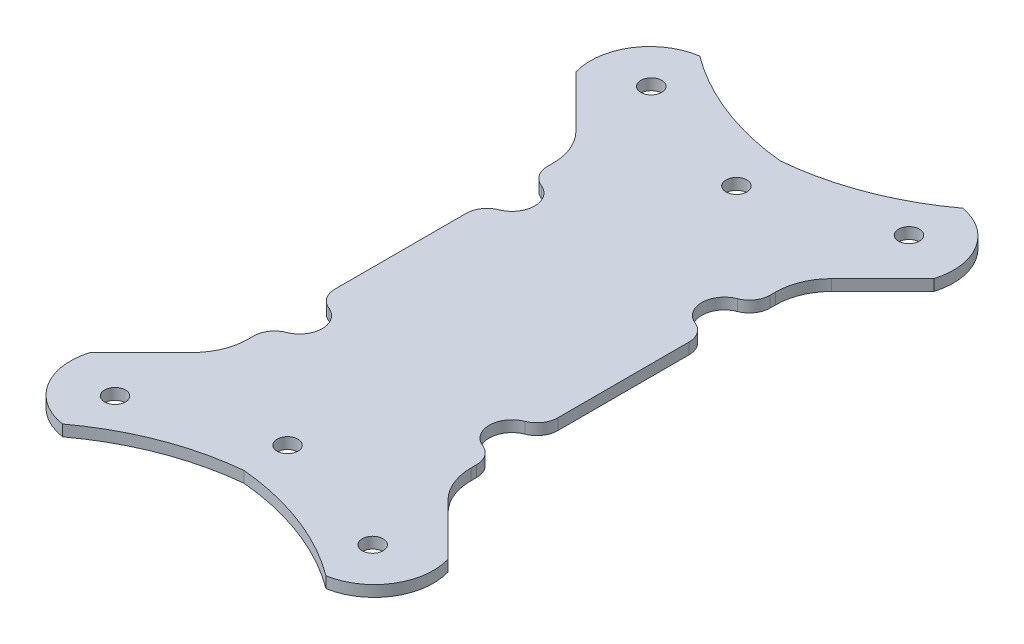
SolidWorks part; units mm, degrees
material "Thornel Mat VMA"
ref_plane "Front Plane" through (0, 0, 0) normal (0, 0, 1) x (1, 0, 0)
ref_plane "Top Plane" through (0, 0, 0) normal (0, 1, 0) x (1, 0, 0)
ref_plane "Right Plane" through (0, 0, 0) normal (1, 0, 0) x (0, 0, -1)
sketch "Sketch1" plane through (0, 0, 0) normal (0, 1, 0) x (1, 0, 0)
  line L0 (123.4756, 1290.8987) -> (175.4725, 1291.4672) construction
  line L1 (167.8436, 1293.6503) -> (130.8436, 1293.6503)
  line L2 (149.3436, 1293.6503) -> (149.3436, 1323.6503) construction
  line L3 (130.5678, 1300.8959) -> (139.0453, 1297.2974)
  line L4 (159.8703, 1297.2612) -> (168.3478, 1300.8597)
  line L7 (123.6486, 1290.0298) -> (131.0005, 1282.6779)
  line L9 (130.8436, 1293.6503) -> (130.8436, 1216.6503) construction
  line L15 (133.3436, 1277.021) -> (133.3436, 1272.6503)
  line L16 (130.8436, 1255.1503) -> (133.3436, 1255.1503) construction
  line L17 (133.3436, 1269.6503) -> (133.3436, 1240.6503)
  line L18 (159.8703, 1213.0394) -> (168.3478, 1209.4409)
  line L19 (130.5678, 1209.4047) -> (139.0453, 1213.0032)
  line L20 (123.6486, 1220.2709) -> (131.0005, 1227.6228)
  line L21 (133.3436, 1233.2796) -> (133.3436, 1237.6503)
  line L22 (175.0387, 1220.2709) -> (167.6868, 1227.6228)
  line L23 (165.3436, 1233.2796) -> (165.3436, 1237.6503)
  line L24 (165.3436, 1269.6503) -> (165.3436, 1240.6503)
  line L25 (165.3436, 1277.021) -> (165.3436, 1272.6503)
  line L26 (175.0387, 1290.0298) -> (167.6868, 1282.6779)
  line L27 (165.3436, 1272.6503) -> (165.3436, 1269.6503)
  line L28 (133.3436, 1272.6503) -> (133.3436, 1269.6503)
  line L29 (133.3436, 1240.6503) -> (133.3436, 1237.6503)
  line L30 (165.3436, 1240.6503) -> (165.3436, 1237.6503)
  circle A0 centre (130.8436, 1293.6503) radius 1.5
  circle A1 centre (167.8436, 1293.6503) radius 1.5
  arc A2 (130.5678, 1300.8959) -> (123.6486, 1290.0298) centre (131.7866, 1292.4838) ccw
  arc A4 (139.0453, 1297.2974) -> (159.8703, 1297.2612) centre (149.4956, 1319.0201) ccw
  arc A5 (175.0387, 1290.0298) -> (168.3478, 1300.8597) centre (166.9007, 1292.4838) ccw
  circle A6 centre (130.8436, 1216.6503) radius 1.5
  circle A7 centre (149.3436, 1287.3814) radius 1.5
  arc A14 (175.0387, 1220.2709) -> (168.3478, 1209.4409) centre (166.9007, 1217.8168) cw
  arc A15 (139.0453, 1213.0032) -> (159.8703, 1213.0394) centre (149.4956, 1191.2805) cw
  arc A17 (130.5678, 1209.4047) -> (123.6486, 1220.2709) centre (131.7866, 1217.8168) cw
  circle A20 centre (149.3436, 1222.9192) radius 1.5
  arc A21 (131.0005, 1227.6228) -> (133.3436, 1233.2796) centre (125.3436, 1233.2796) ccw
  arc A22 (167.6868, 1227.6228) -> (165.3436, 1233.2796) centre (173.3436, 1233.2796) cw
  arc A23 (165.3436, 1277.021) -> (167.6868, 1282.6779) centre (173.3436, 1277.021) cw
  arc A24 (131.0005, 1282.6779) -> (133.3436, 1277.021) centre (125.3436, 1277.021) cw
  circle A25 centre (167.8436, 1216.6503) radius 1.5
  arc A29 (149.3436, 1216.6503) -> (168.3478, 1209.4409) centre (146.0425, 1179.2959) cw
  arc A30 (130.5678, 1209.4047) -> (149.3436, 1216.6503) centre (152.9615, 1179.3252) cw
  arc A31 (149.3436, 1293.6503) -> (168.3478, 1300.8597) centre (146.0425, 1331.0047) ccw
  arc A32 (130.5678, 1300.8959) -> (149.3436, 1293.6503) centre (152.9615, 1330.9754) ccw
  point P54 (133.3436, 1229.9659)
  point P57 (165.3436, 1229.9659)
  point P60 (165.3436, 1280.3347)
  point P63 (133.3436, 1280.3347)
  dimension "D2" = 3
  dimension "D3" = 8
  dimension "D4" = 1.1665
  dimension "D5" = 37
  dimension "D11" = 8.5
  dimension "D13" = 24.1057
  dimension "D20" = 75
  dimension "D19" = 75
  dimension "D1" = 52
  dimension "D6" = 30
  dimension "D7" = 67
  dimension "D8" = 29
  dimension "D9" = 4.3707
  dimension "D10" = 3.6205
  dimension "D12" = 67
  dimension "D14" = 45
  dimension "D15" = 9.2096
  dimension "D16" = 77
  dimension "D18" = 6.2689
  dimension "D22" = 13.7109
extrude "Boss-Extrude1" add sketch "Sketch1" along normal blind 1.6
sketch "Sketch2" plane through (0, 1.6, 0) normal (0, 1, 0) x (1, 0, 0)
  line L0 (133.3436, 1255.1503) -> (165.3436, 1255.1503) construction
  line L1 (133.3436, 1277.021) -> (133.3436, 1233.2796) construction
  line L2 (165.3436, 1233.2796) -> (165.3436, 1277.021) construction
  line L3 (149.3436, 1287.3814) -> (149.3436, 1222.9192) construction
  line L4 (134.0936, 1239.9003) -> (164.5936, 1239.9003) construction
  line L5 (144.3436, 1239.9003) -> (144.3436, 1270.4003) construction
  line L6 (134.0936, 1270.4003) -> (164.5936, 1270.4003) construction
  circle A0 centre (134.0936, 1239.9003) radius 3.25
  circle A1 centre (164.5936, 1239.9003) radius 3.25
  circle A2 centre (164.5936, 1270.4003) radius 3.25
  circle A3 centre (134.0936, 1270.4003) radius 3.25
  point P14 (144.3436, 1255.1503)
  point P21 (149.3436, 1239.9003)
  dimension "D4" = 6.5
  dimension "D1" = 5
  dimension "D2" = 30.5
  dimension "D3" = 30.5
extrude "Cut-Extrude1" cut sketch "Sketch2" against normal up to surface (1.6 mm away) up to face at (149.3634, 0, -1255.1503)
ref_plane "Plane1" through (0, 0, -1255.1503) normal (0, 0, 1) x (1, 0, 0)
ref_plane "Plane2" through (149.3436, 0, 0) normal (1, 0, 0) x (0, 0, -1)
fillet "Fillet1" radius 3 8 edges at (133.3436, 0.8, -1243.0626) (133.3436, 0.8, -1236.738) (133.3436, 0.8, -1273.5626) (133.3436, 0.8, -1267.238) (165.3436, 0.8, -1267.238) (165.3436, 0.8, -1273.5626) (165.3436, 0.8, -1236.738) (165.3436, 0.8, -1243.0626)
